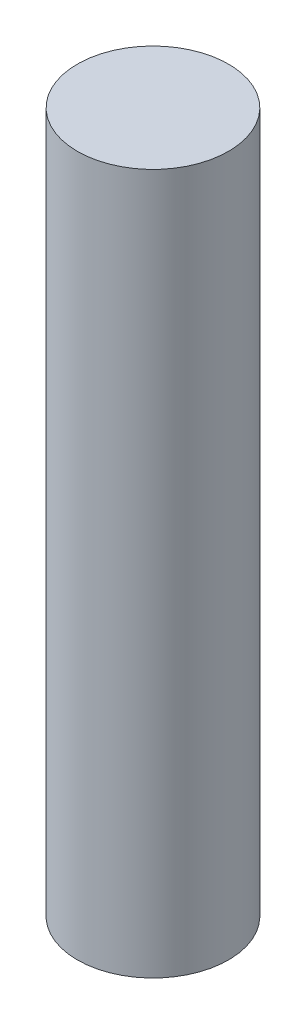
SolidWorks part; units mm, degrees
ref_plane "Front Plane" through (0, 0, 0) normal (0, 0, 1) x (1, 0, 0)
ref_plane "Top Plane" through (0, 0, 0) normal (0, 1, 0) x (1, 0, 0)
ref_plane "Right Plane" through (0, 0, 0) normal (1, 0, 0) x (0, 0, -1)
sketch "Sketch1" plane through (0, 0, 0) normal (0, 1, 0) x (1, 0, 0)
  circle A0 centre (0, 0) radius 4.35
  dimension "D1" = 8.7
extrude "Boss-Extrude1" add sketch "Sketch1" along normal blind 40.3
